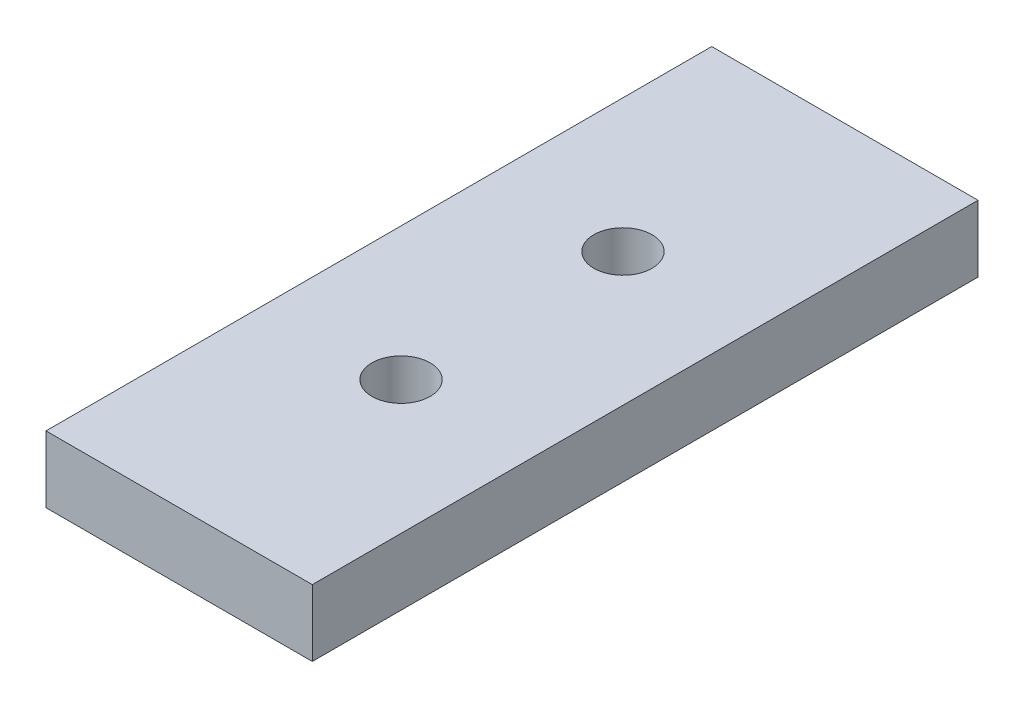
SolidWorks part; units mm, degrees
ref_plane "Front Plane" through (0, 0, 0) normal (0, 0, 1) x (1, 0, 0)
ref_plane "Top Plane" through (0, 0, 0) normal (0, 1, 0) x (1, 0, 0)
ref_plane "Right Plane" through (0, 0, 0) normal (1, 0, 0) x (0, 0, -1)
sketch "Sketch1" plane through (0, 0, 0) normal (0, 1, 0) x (1, 0, 0)
  line L1 (0, 0) -> (-25.4, 0)
  line L2 (0, 0) -> (0, 63.5)
  line L3 (0, 63.5) -> (-25.4, 63.5)
  line L4 (-25.4, 0) -> (-25.4, 63.5)
  dimension "D1" = 63.5
  dimension "D2" = 25.4
extrude "Boss-Extrude2" add sketch "Sketch1" against normal blind 6.35
sketch "Sketch3" plane through (0, 0, 0) normal (0, 1, 0) x (1, 0, 0)
  line L0 (-12.7, 63.5) -> (-12.7, 42.3333) construction
  line L1 (0, 63.5) -> (-25.4, 63.5) construction
  line L2 (-12.7, 0) -> (-12.7, 21.1667) construction
  line L3 (-25.4, 0) -> (0, 0) construction
  line L4 (0, 0) -> (0, 63.5) construction
  circle A0 centre (-12.7, 21.1667) radius 2.7781
  circle A1 centre (-12.7, 42.3333) radius 2.7781
  dimension "D2" = 5.5562
  dimension "D1" = 21.1667
extrude "Cut-Extrude1" cut sketch "Sketch3" against normal through all
